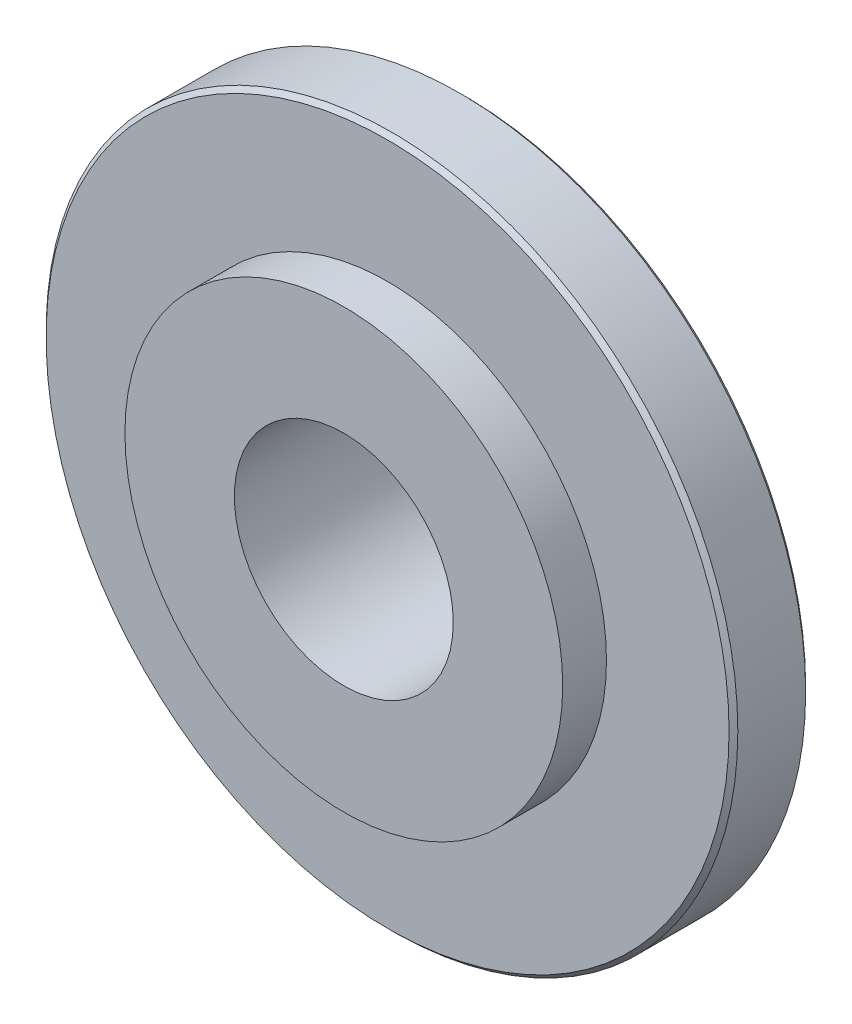
SolidWorks part; units mm, degrees
ref_plane "前视基准面" through (0, 0, 0) normal (0, 0, 1) x (1, 0, 0)
ref_plane "上视基准面" through (0, 0, 0) normal (0, 1, 0) x (1, 0, 0)
ref_plane "右视基准面" through (0, 0, 0) normal (1, 0, 0) x (0, 0, -1)
other "Configuration Table"
sketch "草图1" plane through (0, 0, 0) normal (0, 0, 1) x (1, 0, 0)
  circle A0 centre (0, 0) radius 10
  dimension "D1" = 20
extrude "凸台-拉伸1" add sketch "草图1" along normal blind 2
sketch "草图2" plane through (0, 0, 2) normal (0, 0, 1) x (1, 0, 0)
  circle A0 centre (0, 0) radius 15.8
  dimension "D1" = 31.6
extrude "凸台-拉伸2" add sketch "草图2" along normal blind 3.5
sketch "草图3" plane through (0, 0, 5.5) normal (0, 0, 1) x (1, 0, 0)
  circle A0 centre (0, 0) radius 10
  dimension "D1" = 20
extrude "凸台-拉伸3" add sketch "草图3" along normal blind 2
sketch "草图4" plane through (0, 0, 7.5) normal (0, 0, 1) x (1, 0, 0)
  circle A0 centre (0, 0) radius 5
  dimension "D1" = 10
extrude "切除-拉伸1" cut sketch "草图4" against normal blind 10
chamfer "倒角1" distance 0.2 angle 45 2 edges at (15.8, 0, 2) (15.8, 0, 5.5)
